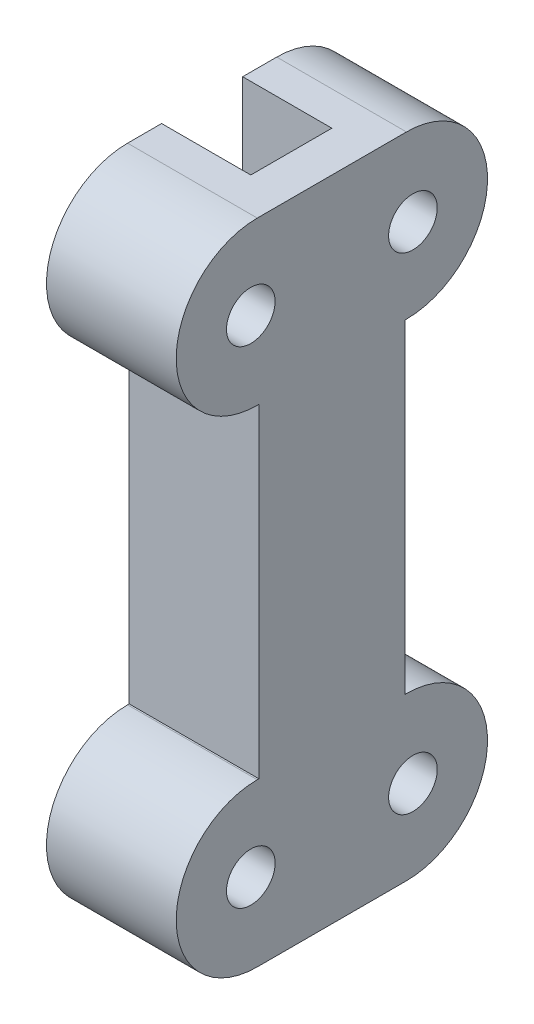
SolidWorks part; units mm, degrees
ref_plane "Front Plane" through (0, 0, 0) normal (0, 0, 1) x (1, 0, 0)
ref_plane "Top Plane" through (0, 0, 0) normal (0, 1, 0) x (1, 0, 0)
ref_plane "Right Plane" through (0, 0, 0) normal (1, 0, 0) x (0, 0, -1)
sketch "Esquisse2" plane through (0, 0, 0) normal (1, 0, 0) x (0, 0, -1)
  line L1 (-4.5, -20) -> (4.5, -20)
  line L2 (-4.5, -20) -> (-4.5, 20)
  line L3 (-4.5, 20) -> (4.5, 20)
  line L4 (4.5, -20) -> (4.5, 20)
  line L5 (-4.5, -20) -> (4.5, 20) construction
  line L6 (-4.5, 20) -> (4.5, -20) construction
  point P0 (0, 0)
  dimension "D1" = 9
  dimension "D2" = 40
extrude "Boss.-Extru.1" add sketch "Esquisse2" along normal blind 8
ref_plane "Plan1" through (0, 0, 0) normal (1, 0, 0) x (0, 0, -1)
sketch "Esquisse3" plane through (0, 0, 0) normal (-1, 0, 0) x (0, 0, 1)
  line L0 (-4.5, 20) -> (4.5, 20) construction
  line L1 (-2.5, -20) -> (2.5, -20)
  line L2 (-2.5, -20) -> (-2.5, 20)
  line L3 (-2.5, 20) -> (2.5, 20)
  line L4 (2.5, -20) -> (2.5, 20)
  line L5 (-2.5, -20) -> (2.5, 20) construction
  line L6 (-2.5, 20) -> (2.5, -20) construction
  point P0 (0, 0)
extrude "Enlèv. mat.-Extru.1" cut sketch "Esquisse3" against normal blind 5.5
sketch "Esquisse4" plane through (0, 0, -4.5) normal (0, 0, -1) x (-1, 0, 0)
  line L1 (0, 20) -> (-8, 20)
  line L2 (0, 20) -> (0, 10)
  line L3 (0, 10) -> (-8, 10)
  line L4 (-8, 20) -> (-8, 10)
extrude "Boss.-Extru.2" add sketch "Esquisse4" along normal blind 0.1
ref_plane "Plan2" through (0, 0, 0) normal (0, 1, 0) x (1, 0, 0)
ref_plane "Plan3" through (0, 0, 0) normal (0, 0, 1) x (1, 0, 0)
sketch "Esquisse13" plane through (0, 0, 0) normal (1, 0, 0) x (0, 0, -1)
  line L0 (4.6, 10) -> (4.6, 20) construction
  line L6 (2.5, 20) -> (2.5, -20)
  line L7 (4.6, 20) -> (2.5, 20)
  line L8 (4.6, 10) -> (4.6, 20)
  line L9 (4.5, 10) -> (4.6, 10)
  line L10 (4.5, -20) -> (4.5, 10)
  line L11 (2.5, -20) -> (4.5, -20)
  line L14 (4.6, 10) -> (4.6, 20)
  arc A0 (4.6, 20) -> (4.6, 10) centre (4.6, 15) cw
  point P4 (0, 0)
  point P5 (0, 0)
  point P7 (4.6, 15)
  dimension "D1" = 0
extrude "Boss.-Extru.5" add sketch "Esquisse13" along normal blind 8
sketch "Esquisse14" plane through (0, 0, 0) normal (-1, 0, 0) x (0, 0, 1)
  line L0 (-9.6, 15) -> (-0.4, 15) construction
  line L1 (0, -4.4) -> (0, 4.4) construction
  arc A0 (-4.6, 20) -> (-4.6, 10) centre (-4.6, 15) ccw construction
  circle A1 centre (-5, 15) radius 1.5
  dimension "D1" = 5
extrude "Enlèv. mat.-Extru.4" cut sketch "Esquisse14" against normal through all
mirror "Symétrie4" about plane through (0, 0, 0) normal (0, 0, 1) of "Boss.-Extru.2", "Enlèv. mat.-Extru.4", "Boss.-Extru.5"
mirror "Symétrie5" about plane through (0, 0, 0) normal (0, 1, 0) of "Symétrie4", "Boss.-Extru.2", "Boss.-Extru.5", "Enlèv. mat.-Extru.4"
